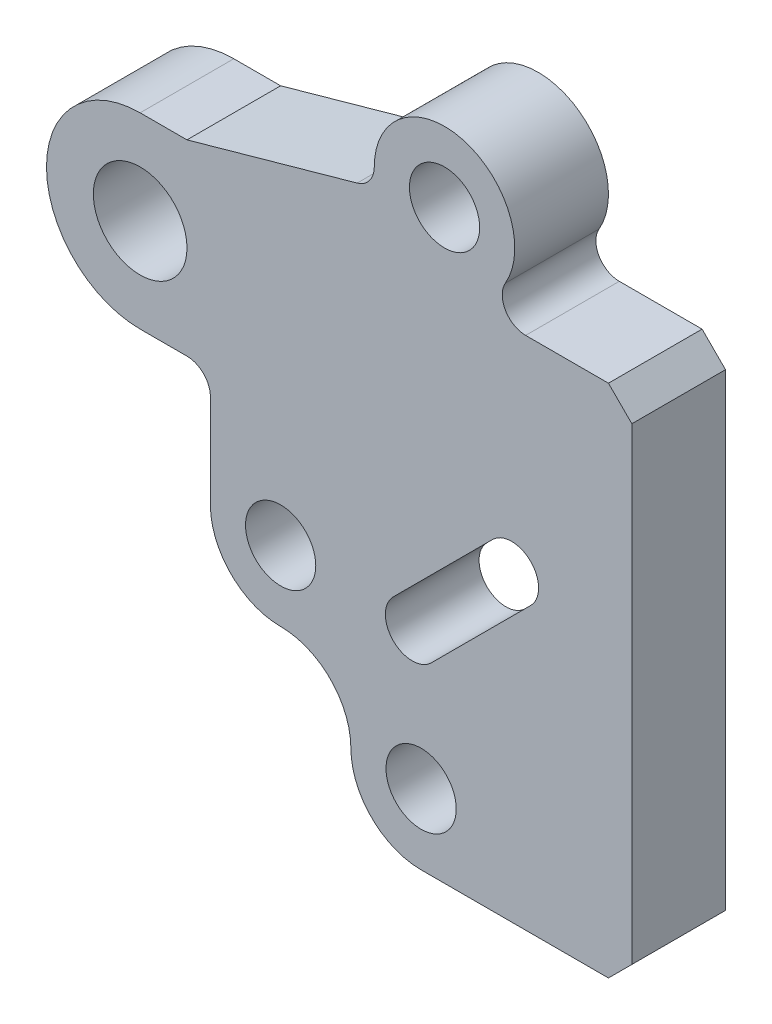
SolidWorks part; units mm, degrees
ref_plane "Front Plane" through (0, 0, 0) normal (0, 0, 1) x (1, 0, 0)
ref_plane "Top Plane" through (0, 0, 0) normal (0, 1, 0) x (1, 0, 0)
ref_plane "Right Plane" through (0, 0, 0) normal (1, 0, 0) x (0, 0, -1)
sketch "Sketch1" plane through (0, 0, 0) normal (0, 0, 1) x (1, 0, 0)
  line L0 (0, -20) -> (10, -20)
  line L1 (15, -25) -> (15, -45)
  line L2 (60, -90) -> (100, -90)
  line L3 (105, -85) -> (105, 15)
  line L4 (0, 20) -> (10, 20)
  line L5 (108.1937, 35) -> (-31.0694, 35) construction
  line L6 (10, 20) -> (46.3491, 30.1854)
  line L7 (100, 20) -> (82.3205, 20)
  line L8 (105, 15) -> (100, 20)
  line L9 (100, -90) -> (105, -85)
  line L10 (58.1197, -46.5521) -> (79.3329, -25.3389) construction
  line L11 (54.0536, -42.4861) -> (75.2668, -21.2728)
  line L12 (62.1858, -50.6182) -> (83.399, -29.405)
  line L13 (-24.7982, 0) -> (76.0757, 0) construction
  circle A0 centre (0, 0) radius 10
  arc A1 (0, 20) -> (0, -20) centre (0, 0) ccw
  arc A2 (77.9904, 27.5) -> (50, 35) centre (65, 35) ccw
  circle A3 centre (65, 35) radius 7.5
  circle A4 centre (30, -45) radius 7.5
  arc A5 (15, -45) -> (30, -60) centre (30, -45) ccw
  arc A6 (45, -75) -> (60, -90) centre (60, -75) ccw
  circle A7 centre (60, -75) radius 7.5
  arc A8 (45, -75) -> (30, -60) centre (30, -75) ccw
  arc A10 (77.9904, 27.5) -> (82.3205, 20) centre (82.3205, 25) ccw
  arc A11 (15, -25) -> (10, -20) centre (10, -25) ccw
  arc A12 (40, 35) -> (50, 35) centre (45, 35) ccw
  arc A13 (54.0536, -42.4861) -> (62.1858, -50.6182) centre (58.1197, -46.5521) ccw
  arc A14 (83.399, -29.405) -> (75.2668, -21.2728) centre (79.3329, -25.3389) ccw
  point P17 (105, -90)
  point P24 (105, 20)
  point P28 (68.7263, -35.9455)
  point P44 (0, 0)
  dimension "D2" = 40
  dimension "D3" = 20
  dimension "D4" = 30
  dimension "D5" = 15
  dimension "D6" = 15
  dimension "D7" = 30
  dimension "D8" = 30
  dimension "D9" = 30
  dimension "D10" = 15
  dimension "D11" = 10
  dimension "D12" = 10
  dimension "D13" = 5
  dimension "D14" = 10
  dimension "D17" = 5.7503
  dimension "D26" = 40
  dimension "D1" = 90
  dimension "D15" = 30
  dimension "D18" = 30
  dimension "D19" = 75
  dimension "D20" = 15
  dimension "D21" = 45
  dimension "D22" = 105
  dimension "D23" = 65
  dimension "D24" = 35
  dimension "D27" = 45
  dimension "D28" = 46.8803
extrude "Boss-Extrude1" add sketch "Sketch1" along normal mid plane 20 contours A12 L6 L4 A1 L0 A11 L1 A5 A8 A6 L2 L9 L3 L8 L7 A10 A2 A14 L12 A13 L11 A7 A4 A3 A0
